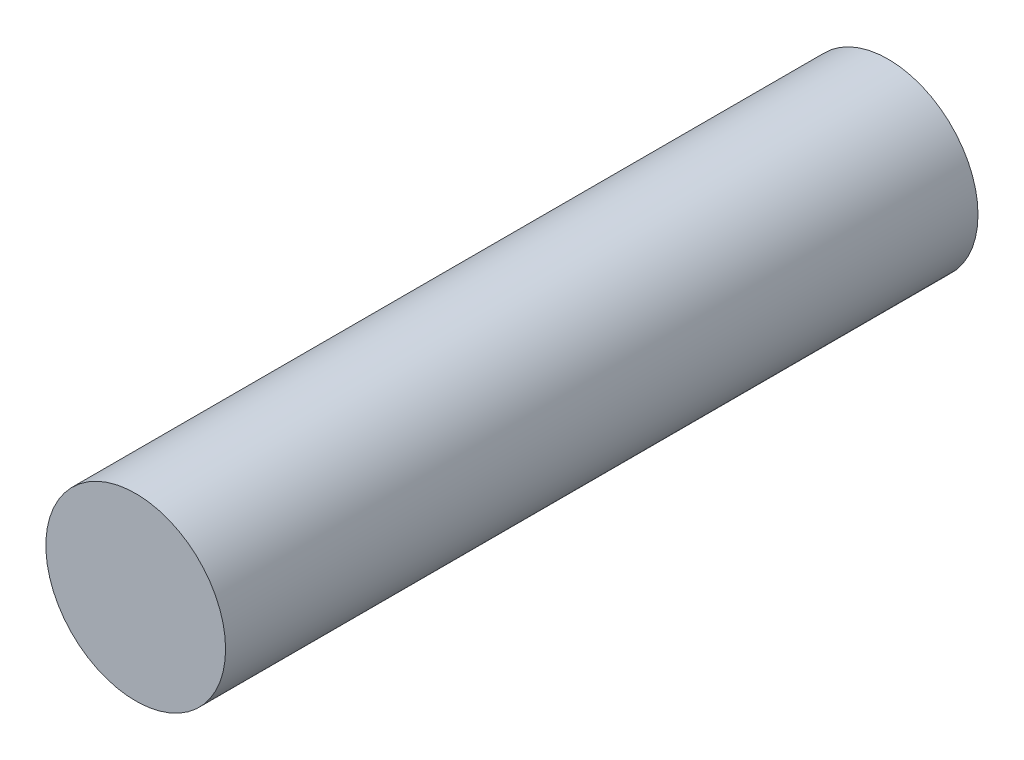
SolidWorks part; units mm, degrees
ref_plane "Front Plane" through (0, 0, 0) normal (0, 0, 1) x (1, 0, 0)
ref_plane "Top Plane" through (0, 0, 0) normal (0, 1, 0) x (1, 0, 0)
ref_plane "Right Plane" through (0, 0, 0) normal (1, 0, 0) x (0, 0, -1)
sketch "Sketch1" plane through (0, 0, 0) normal (0, 0, 1) x (1, 0, 0)
  circle A0 centre (0, 0) radius 2.15
extrude "Boss-Extrude1" add sketch "Sketch1" along normal blind 18
